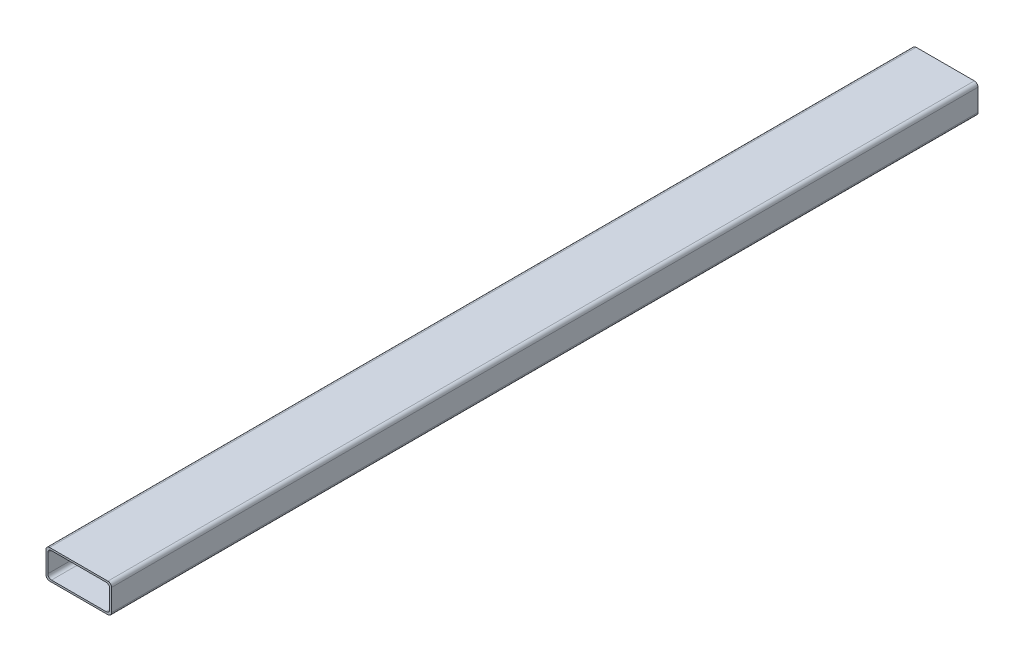
SolidWorks part; units mm, degrees
material "Plain Carbon Steel"
ref_plane "Front Plane" through (0, 0, 0) normal (0, 0, 1) x (1, 0, 0)
ref_plane "Top Plane" through (0, 0, 0) normal (0, 1, 0) x (1, 0, 0)
ref_plane "Right Plane" through (0, 0, 0) normal (1, 0, 0) x (0, 0, -1)
sketch "Sketch1" plane through (0, 0, 0) normal (0, 0, 1) x (1, 0, 0)
  line L1 (-53.975, -22.225) -> (53.975, -22.225)
  line L2 (-53.975, -22.225) -> (-53.975, 22.225)
  line L3 (-53.975, 22.225) -> (53.975, 22.225)
  line L4 (53.975, -22.225) -> (53.975, 22.225)
  line L5 (-53.975, -22.225) -> (53.975, 22.225) construction
  line L6 (-53.975, 22.225) -> (53.975, -22.225) construction
  line L7 (-57.15, -25.4) -> (57.15, -25.4)
  line L8 (-57.15, -25.4) -> (-57.15, 25.4)
  line L9 (-57.15, 25.4) -> (57.15, 25.4)
  line L10 (57.15, -25.4) -> (57.15, 25.4)
  line L11 (-57.15, -25.4) -> (57.15, 25.4) construction
  line L12 (-57.15, 25.4) -> (57.15, -25.4) construction
  point P0 (0, 0)
  point P5 (0, 0)
  dimension "D1" = 3.175
  dimension "D2" = 3.175
  dimension "D3" = 114.3
  dimension "D4" = 50.8
extrude "Boss-Extrude1" add sketch "Sketch1" along normal blind 1511.3
fillet "Fillet1" radius 6.35 8 edges at (53.975, 22.225, 755.65) (53.975, -22.225, 755.65) (-53.975, -22.225, 755.65) (-53.975, 22.225, 755.65) (-57.15, -25.4, 755.65) (57.15, -25.4, 755.65) (-57.15, 25.4, 755.65) (57.15, 25.4, 755.65)
hole_wizard "1/2 Clearance Hole1" positions "Sketch2" profile "Sketch4" hole size "1/2" standard "ANSI Inch"
sketch "Sketch2" plane through (-57.15, 0, 0) normal (-1, 0, 0) x (0, 0, 1)
  line L0 (0, 9.525) -> (251.8833, 9.525) construction
  line L3 (755.65, 9.525) -> (1007.5333, 9.525) construction
  line L4 (1007.5333, 9.525) -> (1259.4167, 9.525) construction
  line L5 (1259.4167, 9.525) -> (1511.3, 9.525) construction
  line L7 (251.8833, 9.525) -> (503.7667, 9.525) construction
  line L8 (503.7667, 9.525) -> (755.65, 9.525) construction
  line L9 (0, -19.05) -> (1511.3, -19.05) construction
  line L10 (1511.3, 19.05) -> (1511.3, -19.05) construction
  point P0 (251.8833, 9.525)
  point P2 (503.7667, 9.525)
  point P4 (755.65, 9.525)
  point P6 (1007.5333, 9.525)
  point P8 (1259.4167, 9.525)
  point P45 (1511.3, 0)
  dimension "D1" = 19.05
sketch "Sketch4" plane through (-57.15, 9.525, 251.8833) normal (0, 1, 0) x (0, 0, 1)
  line L0 (0, 0) -> (0, 114.3)
  line L1 (0, 114.3) -> (6.9456, 114.3)
  line L2 (6.9456, 114.3) -> (6.9456, 0)
  line L5 (6.9456, 0) -> (0, 0)
  line L11 (0, -6.35) -> (0, 107.95) construction
  dimension "Thru Hole Dia." = 13.8913
  dimension "Thru Hole Depth" = 114.3
